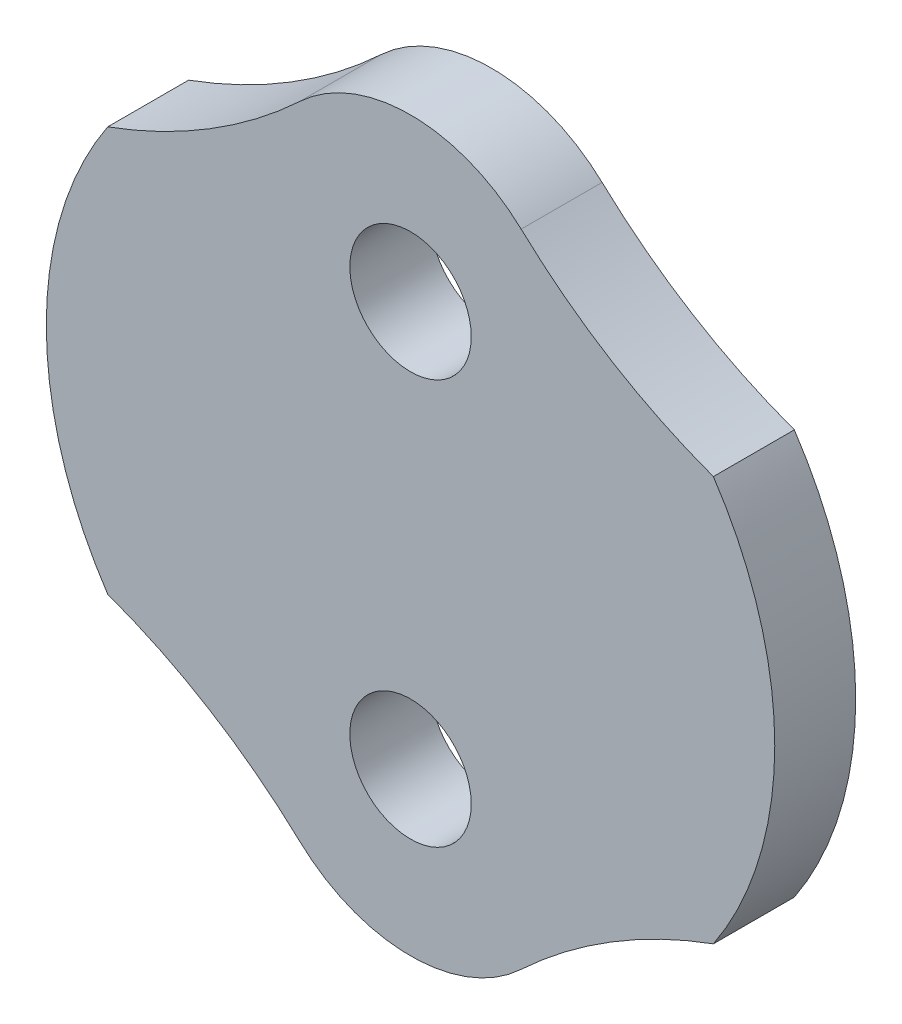
SolidWorks part; units mm, degrees
ref_plane "Front Plane" through (0, 0, 0) normal (0, 0, 1) x (1, 0, 0)
ref_plane "Top Plane" through (0, 0, 0) normal (0, 1, 0) x (1, 0, 0)
ref_plane "Right Plane" through (0, 0, 0) normal (1, 0, 0) x (0, 0, -1)
sketch "Sketch1" plane through (0, 0, 0) normal (0, 0, 1) x (1, 0, 0)
  circle A0 centre (0, 0) radius 14.2875
  circle A1 centre (0, 7.9375) radius 2.3812
  circle A2 centre (0, -7.9375) radius 2.3812
  dimension "D1" = 4.7625
  dimension "D2" = 4.7625
  dimension "D3" = 15.875
  dimension "D5" = 28.575
  dimension "D4" = 7.9375
extrude "Boss-Extrude1" add sketch "Sketch1" along normal blind 3.175
sketch "Sketch2" plane through (0, 0, 3.175) normal (0, 0, 1) x (1, 0, 0)
  line L0 (0, 0) -> (0, 3.8528)
  line L1 (-11.8798, 7.9375) -> (11.8798, 7.9375)
  line L2 (-11.8798, 7.9375) -> (-11.8798, -7.9375)
  line L3 (-11.8798, -7.9375) -> (11.8798, -7.9375)
  line L4 (11.8798, 7.9375) -> (11.8798, -7.9375)
  line L5 (0, 0) -> (-3.248, 0)
  circle A0 centre (0, 7.9375) radius 6.35
  circle A1 centre (0, -7.9375) radius 6.35
  circle A2 centre (0, 0) radius 14.2875 construction
  arc A3 (-11.8798, 7.9375) -> (-4.3401, 12.5728) centre (-19.4681, 28.73) ccw
  arc A4 (11.8798, 7.9375) -> (4.3401, 12.5728) centre (19.4681, 28.73) cw
  arc A5 (11.8798, -7.9375) -> (4.3401, -12.5728) centre (19.4681, -28.73) ccw
  arc A6 (-11.8798, -7.9375) -> (-4.3401, -12.5728) centre (-19.4681, -28.73) cw
  circle A7 centre (0, 0) radius 18.8322
  arc A8 (-11.8798, 7.9375) -> (-11.8798, -7.9375) centre (0, 0) ccw
  arc A9 (11.8798, -7.9375) -> (11.8798, 7.9375) centre (0, 0) ccw
  arc A10 (-11.8798, 7.9375) -> (-11.8798, -7.9375) centre (0, 0) ccw
  arc A11 (11.8798, -7.9375) -> (11.8798, 7.9375) centre (0, 0) ccw
  circle M6 centre (0, 0) radius 14.2875
extrude "Cut-Extrude1" cut sketch "Sketch2" against normal through all contours A3 A0 M6 | A6 A1 M6 | A5 A1 M6 | A4 A0 M6 | A7 M6
